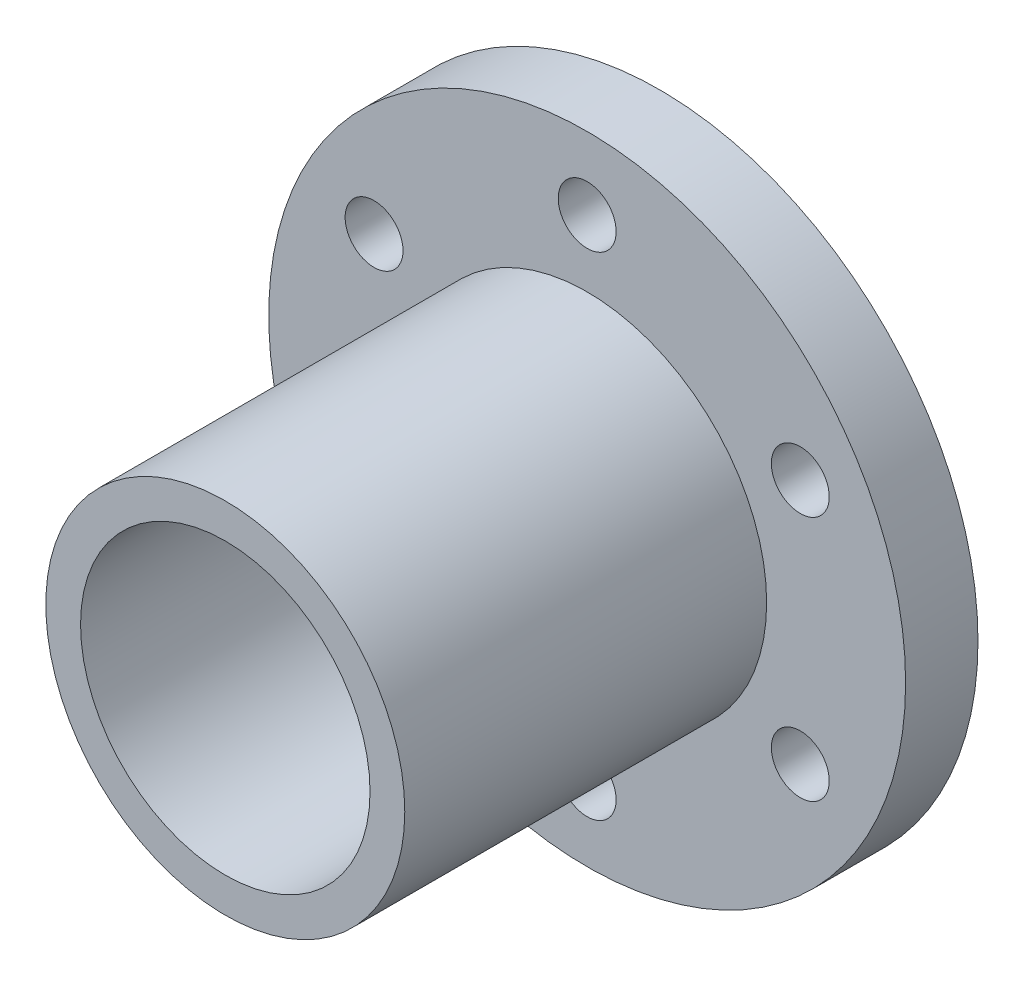
SolidWorks part; units mm, degrees
ref_plane "Front Plane" through (0, 0, 0) normal (0, 0, 1) x (1, 0, 0)
ref_plane "Top Plane" through (0, 0, 0) normal (0, 1, 0) x (1, 0, 0)
ref_plane "Right Plane" through (0, 0, 0) normal (1, 0, 0) x (0, 0, -1)
sketch "Sketch1" plane through (0, 0, 0) normal (0, 0, 1) x (1, 0, 0)
  circle A0 centre (0, 0) radius 110
  dimension "D1" = 220
extrude "Boss-Extrude1" add sketch "Sketch1" along normal blind 25
sketch "Sketch2" plane through (0, 0, 25) normal (0, 0, 1) x (1, 0, 0)
  circle A0 centre (0, 0) radius 62
  dimension "D1" = 124
extrude "Boss-Extrude2" add sketch "Sketch2" along normal blind 125
sketch "Sketch3" plane through (0, 0, 150) normal (0, 0, 1) x (1, 0, 0)
  circle A0 centre (0, 0) radius 50
  dimension "D1" = 100
extrude "Cut-Extrude1" cut sketch "Sketch3" against normal through all
sketch "Sketch4" plane through (0, 0, 25) normal (0, 0, 1) x (1, 0, 0)
  circle A0 centre (0, 0) radius 85
  circle A1 centre (0, 85) radius 10
  circle A2 centre (73.6122, 42.5) radius 10
  circle A3 centre (73.6122, -42.5) radius 10
  circle A4 centre (0, -85) radius 10
  circle A5 centre (-73.6122, -42.5) radius 10
  circle A6 centre (-73.6122, 42.5) radius 10
  point P18 (0, 0)
  dimension "D1" = 170
  dimension "D2" = 20
  dimension "D3" = 6
extrude "Cut-Extrude2" cut sketch "Sketch4" against normal through all contours A0 A6 | A0 A6 | A0 A1 | A0 A1 | A0 A5 | A0 A5 | A0 A4 | A0 A4 | A0 A3 | A0 A3 | A0 A2 | A0 A2
